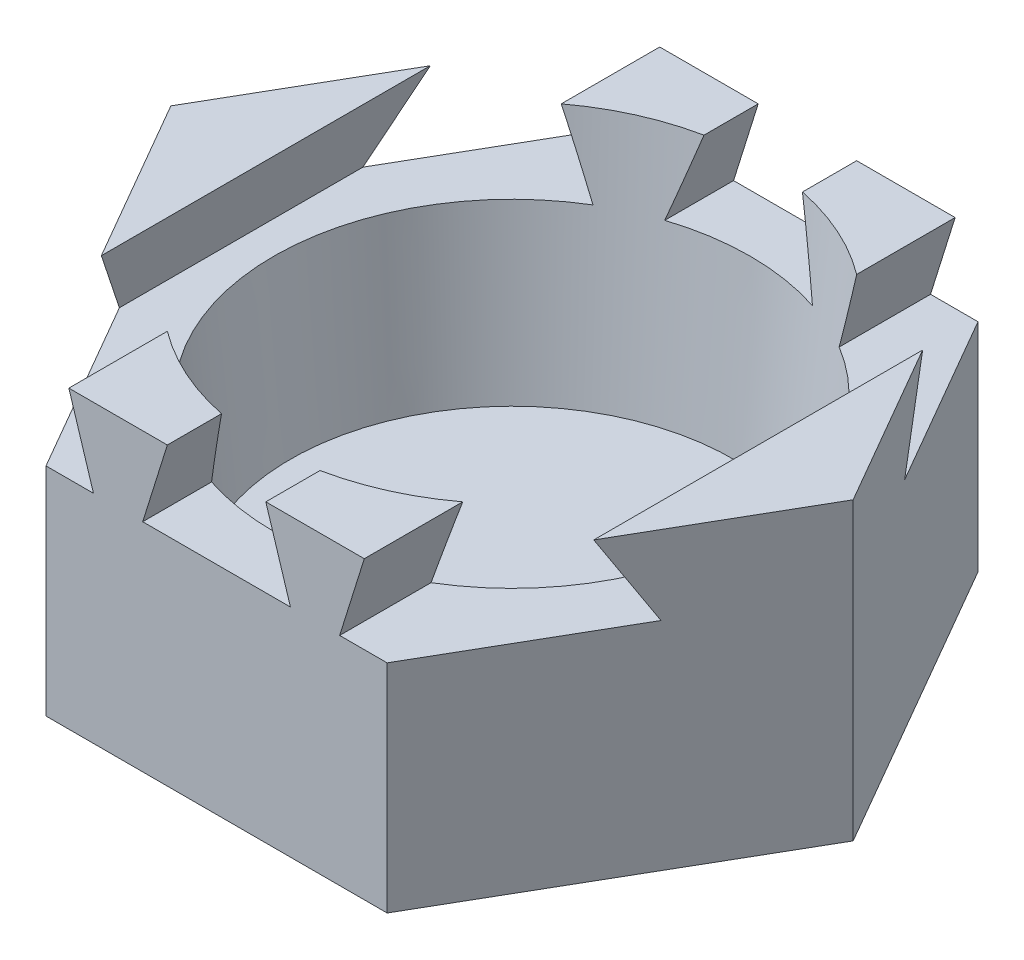
SolidWorks part; units mm, degrees
ref_plane "前基準面" through (0, 0, 0) normal (0, 0, 1) x (1, 0, 0)
ref_plane "上基準面" through (0, 0, 0) normal (0, 1, 0) x (1, 0, 0)
ref_plane "右基準面" through (0, 0, 0) normal (1, 0, 0) x (0, 0, -1)
sketch "草圖1" plane through (0, 0, 0) normal (0, 1, 0) x (1, 0, 0)
  line L0 (-34.641, 0) -> (-30, 0)
  line L1 (17.3205, -30) -> (34.641, 0)
  line L2 (34.641, 0) -> (17.3205, 30)
  line L3 (17.3205, 30) -> (-17.3205, 30)
  line L4 (-17.3205, 30) -> (-34.641, 0)
  line L5 (-34.641, 0) -> (-17.3205, -30)
  line L6 (-17.3205, -30) -> (17.3205, -30)
  line L7 (30, 0) -> (34.641, 0)
  circle A0 centre (0, 0) radius 30 construction
  dimension "D1" = 60
extrude "填料-伸長1" add sketch "草圖1" along normal blind 30
sketch "草圖2" plane through (0, 0, 0) normal (0, 0, 1) x (1, 0, 0)
  line L0 (0, 31.5469) -> (0, 0) construction
  line L1 (0, 30) -> (25, 30)
  line L2 (-17.3205, 30) -> (17.3205, 30) construction
  line L3 (17.3205, 30) -> (34.641, 30) construction
  line L4 (25, 30) -> (22.5, 5)
  line L5 (22.5, 5) -> (0, 5)
  line L6 (0, 5) -> (0, 30)
  line L7 (-17.3205, 0) -> (17.3205, 0) construction
  dimension "D1" = 25
  dimension "D2" = 22.5
  dimension "D3" = 5
revolve "除料-旋轉1" cut sketch "草圖2" angle 360 about L6
sketch "草圖3" plane through (0, 0, 0) normal (0, 0, 1) x (1, 0, 0)
  line L0 (0, 30) -> (0, 0) construction
  line L1 (-17.3205, 30) -> (17.3205, 30) construction
  line L2 (-5, 30) -> (-7.5, 22)
  line L3 (-7.5, 22) -> (7.5, 22)
  line L4 (7.5, 22) -> (5, 30)
  line L5 (5, 30) -> (-5, 30)
  point P7 (0, 30)
  point P10 (0, 22)
  dimension "D1" = 10
  dimension "D2" = 15
  dimension "D3" = 8
extrude "除料-伸長1" cut sketch "草圖3" against normal through all both and the other way through all
pattern_linear "直線複製排列1" count 2 spacing 20 along (-1, 0, 0) of "除料-伸長1"
pattern_linear "直線複製排列2" count 2 spacing 20 along (1, 0, 0) of "直線複製排列1"
